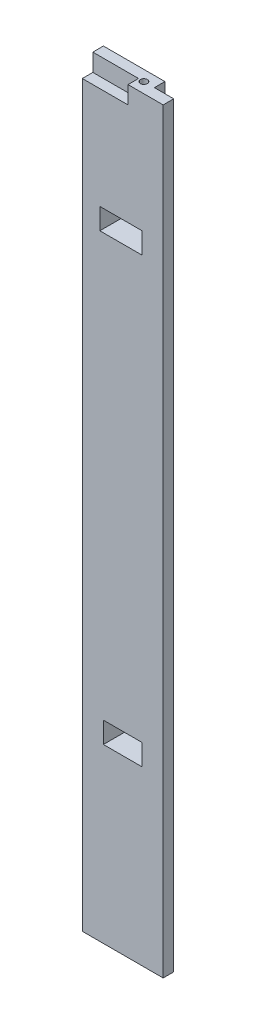
SolidWorks part; units mm, degrees
material "Plywood"
ref_plane "Plan de face" through (0, 0, 0) normal (0, 0, 1) x (1, 0, 0)
ref_plane "Plan de dessus" through (0, 0, 0) normal (0, 1, 0) x (1, 0, 0)
ref_plane "Plan de droite" through (0, 0, 0) normal (1, 0, 0) x (0, 0, -1)
sketch "Esquisse1" plane through (0, 0, 0) normal (0, 1, 0) x (1, 0, 0)
  line L0 (0, 0) -> (0, 6)
  line L1 (0, 6) -> (17.5, 6)
  line L2 (17.5, 6) -> (17.5, 3)
  line L3 (17.5, 3) -> (23, 3)
  line L4 (23, 3) -> (23, 0)
  line L5 (23, 0) -> (0, 0)
  dimension "D1" = 6
  dimension "D2" = 3
  dimension "D3" = 5.5
  dimension "D4" = 23
extrude "Boss.-Extru.1" add sketch "Esquisse1" along normal blind 215
sketch "Esquisse2" plane through (0, 215, 0) normal (0, 1, 0) x (1, 0, 0)
  line L1 (0, 0) -> (13, 0)
  line L2 (0, 0) -> (0, 3)
  line L3 (0, 3) -> (13, 3)
  line L4 (13, 0) -> (13, 3)
  dimension "D1" = 3
  dimension "D2" = 13
extrude "Enlèv. mat.-Extru.1" cut sketch "Esquisse2" against normal blind 5
sketch "Esquisse3" plane through (0, 0, 0) normal (0, 0, 1) x (1, 0, 0)
  line L0 (25.5, 175) -> (0, 175) construction
  line L1 (17, 175) -> (5, 175)
  line L2 (17, 175) -> (17, 181)
  line L3 (17, 181) -> (5, 181)
  line L4 (5, 175) -> (5, 181)
  line L5 (23, 215) -> (23, 0) construction
  dimension "D1" = 6
  dimension "D2" = 6
  dimension "D3" = 12
extrude "Enlèv. mat.-Extru.2" cut sketch "Esquisse3" against normal through all
sketch "Esquisse4" plane through (0, 215, 0) normal (0, 1, 0) x (1, 0, 0)
  line L0 (23, 3) -> (17.5, 3) construction
  line L1 (13, 0) -> (13, 3) construction
  circle A0 centre (14.5, 3) radius 1
  dimension "D2" = 2
  dimension "D1" = 1.5
extrude "Enlèv. mat.-Extru.3" cut sketch "Esquisse4" against normal blind 10
sketch "Esquisse5" plane through (0, 0, -6) normal (0, 0, -1) x (-1, 0, 0)
  line L1 (-6, 49) -> (-17, 49)
  line L2 (-6, 49) -> (-6, 55)
  line L3 (-6, 55) -> (-17, 55)
  line L4 (-17, 49) -> (-17, 55)
extrude "Enlèv. mat.-Extru.4" cut sketch "Esquisse5" against normal through all both and the other way through all
